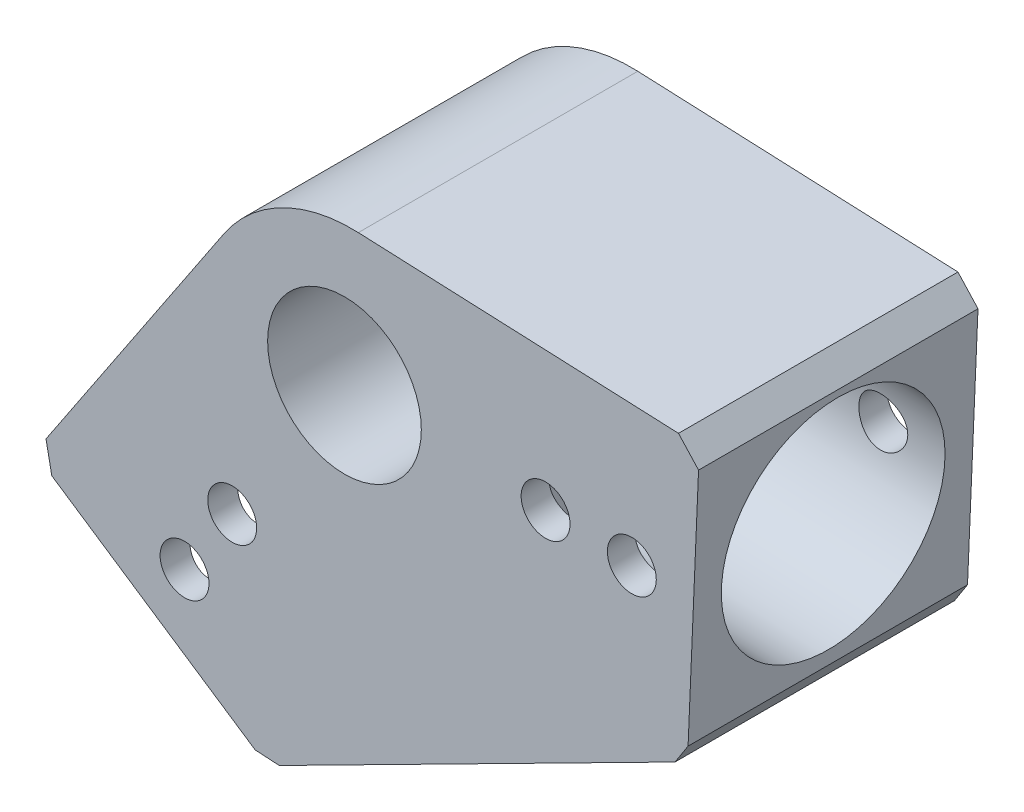
SolidWorks part; units mm, degrees
ref_plane "Front Plane" through (0, 0, 0) normal (0, 0, 1) x (1, 0, 0)
ref_plane "Top Plane" through (0, 0, 0) normal (0, 1, 0) x (1, 0, 0)
ref_plane "Right Plane" through (0, 0, 0) normal (1, 0, 0) x (0, 0, -1)
sketch "Sketch8" plane through (0, 0, 0) normal (0, 0, 1) x (1, 0, 0)
  line L0 (0, 0) -> (-27754.7111, -41589.3738) construction
  line L1 (0, 0) -> (49954.0261, -2143.6585) construction
  line L2 (-44.3905, -30.4875) -> (-11.119, -52.6913)
  line L3 (50.8115, 17.838) -> (49.0966, -22.1253)
  line L4 (-11.119, -52.6913) -> (49.0966, -22.1253)
  line L5 (50.8115, 17.838) -> (-44.3905, -30.4875)
  line L6 (-44.3905, -30.4875) -> (50.8115, 17.838)
  line L7 (-44.3905, -30.4875) -> (-57.9695, -3.7366)
  line L8 (50.8115, 17.838) -> (37.2325, 44.5888)
  line L9 (-57.9695, -3.7366) -> (37.2325, 44.5888)
  point P8 (-27.7547, -41.5894)
  point P11 (49.954, -2.1437)
  dimension "D1" = 121.26
  dimension "D2" = 40
  dimension "D3" = 40
  dimension "D4" = 50
  dimension "D5" = 50
  dimension "D6" = 30
extrude "Boss-Extrude6" add sketch "Sketch8" along normal blind 40 contours L9 L7 L5 L8 | L3 L5 L2 L4
sketch "Sketch9" plane through (-27.7547, -41.5894, 0) normal (-0.5551, -0.8318, 0) x (-0.8318, 0.5551, 0)
  line L0 (20, -40) -> (-20, -40) construction
  line L1 (-20, -40) -> (-20, 0) construction
  circle A0 centre (0, -20) radius 16
  dimension "D1" = 32
  dimension "D2" = 20
  dimension "D3" = 20
extrude "Cut-Extrude3" cut sketch "Sketch9" against normal blind 30
sketch "Sketch10" plane through (49.954, -2.1437, 0) normal (0.9991, -0.0429, 0) x (0, 0, -1)
  line L0 (0, 20) -> (0, -20) construction
  line L1 (-40, -20) -> (0, -20) construction
  line L2 (-40, 20) -> (-40, -20) construction
  circle A0 centre (-20, 0) radius 16
  dimension "D1" = 32
  dimension "D2" = 20
  dimension "D3" = 20
extrude "Cut-Extrude4" cut sketch "Sketch10" against normal blind 30
sketch "Sketch11" plane through (0, 0, 0) normal (0, 0, -1) x (-1, 0, 0)
  circle A0 centre (16.0723, -23.9825) radius 3.5
  circle A1 centre (22.8948, -34.2649) radius 3.5
  circle A2 centre (-28.7829, -1.0657) radius 3.5
  circle A3 centre (-41.1318, -1.7652) radius 3.5
  dimension "D1" = 7
  dimension "D2" = 7
  dimension "D11" = 7
  dimension "D12" = 7
extrude "Cut-Extrude5" cut sketch "Sketch11" against normal up to surface (40 mm away) up to face at (3.9436, -7.769, 40)
sketch "Sketch12" plane through (0, 0, 0) normal (0, 0, -1) x (-1, 0, 0)
  line L1 (44.3905, -30.4875) -> (57.9695, -3.7366) construction
  line L3 (27.7547, -41.5894) -> (27782.4658, -41630.9631) construction
  line L4 (44.3905, -30.4875) -> (11.119, -52.6913) construction
  line L5 (-49.954, -2.1437) -> (-50003.9802, -2145.8021) construction
  line L6 (-50.8115, 17.838) -> (-49.0966, -22.1253) construction
  circle A0 centre (0.0022, -0.0011) radius 11
  point P10 (27.7547, -41.5894)
  point P15 (-49.954, -2.1437)
  dimension "D1" = 22
  dimension "D2" = 53.38
extrude "Cut-Extrude6" cut sketch "Sketch12" against normal up to surface (40 mm away) up to face at (44.6318, -1.7652, 40)
sketch "Sketch14" plane through (-10.3685, 20.4261, 0) normal (-0.4526, 0.8917, 0) x (0.8917, 0.4526, 0)
  line L1 (53.3825, -40) -> (-53.3825, -40)
  line L2 (53.3825, -40) -> (53.3825, 0)
  line L3 (53.3825, 0) -> (-53.3825, 0)
  line L4 (-53.3825, -40) -> (-53.3825, 0)
  line L5 (0, 0) -> (0, -40) construction
  line L6 (53.3825, -20) -> (-53.3825, -20) construction
  point P364 (0, -20)
extrude "Boss-Extrude7" add sketch "Sketch14" along normal blind 5
sketch "Sketch15" plane through (0, 0, 0) normal (0, 0, -1) x (-1, 0, 0)
  line L0 (-50.8115, 17.838) -> (20.4863, 20.8975)
  line L1 (-34.9693, 49.0473) -> (60.2326, 0.7219) construction
  line L2 (44.3905, -30.4875) -> (4.7771, 28.8717)
  line L3 (-50.8115, 17.838) -> (-49.0966, -22.1253) construction
  line L4 (44.3905, -30.4875) -> (11.119, -52.6913) construction
  line L5 (44.3905, -30.4875) -> (60.2326, 0.7219)
  line L6 (60.2326, 0.7219) -> (-34.9693, 49.0473)
  line L7 (-34.9693, 49.0473) -> (-50.8115, 17.838)
  line M11 (44.3905, -30.4875) -> (60.2326, 0.7219)
  line M12 (60.2326, 0.7219) -> (-34.9693, 49.0473)
  line M13 (-34.9693, 49.0473) -> (-50.8115, 17.838)
extrude "Cut-Extrude8" cut sketch "Sketch15" against normal up to surface (40 mm away) contours L2 L0 M11 M12 | L0 L2 M12 M13 | L2 L0 M12 up to face at (10.9978, -0.0011, 40)
fillet "Fillet1" radius 22 1 edges at (-10.3878, 20.4642, 20)
chamfer "Chamfer5" distance 2 2 edges at (-11.119, -52.6913, 20) (49.0966, -22.1253, 20)
chamfer "Chamfer6" distance 3 angle 45 2 edges at (50.8115, 17.838, 20) (-44.3905, -30.4875, 20)
sketch "Sketch16" plane through (18.9888, -37.4083, 0) normal (0.4526, -0.8917, 0) x (-0.8917, -0.4526, 0)
  line L0 (31.7646, -40) -> (-31.7646, -40) construction
  line L2 (-31.7646, 0) -> (-31.7646, -40) construction
  circle A0 centre (-1.7646, -20) radius 5
  dimension "D1" = 10
  dimension "D3" = 30
  dimension "D2" = 20
extrude "Cut-Extrude9" cut sketch "Sketch16" against normal blind 27
